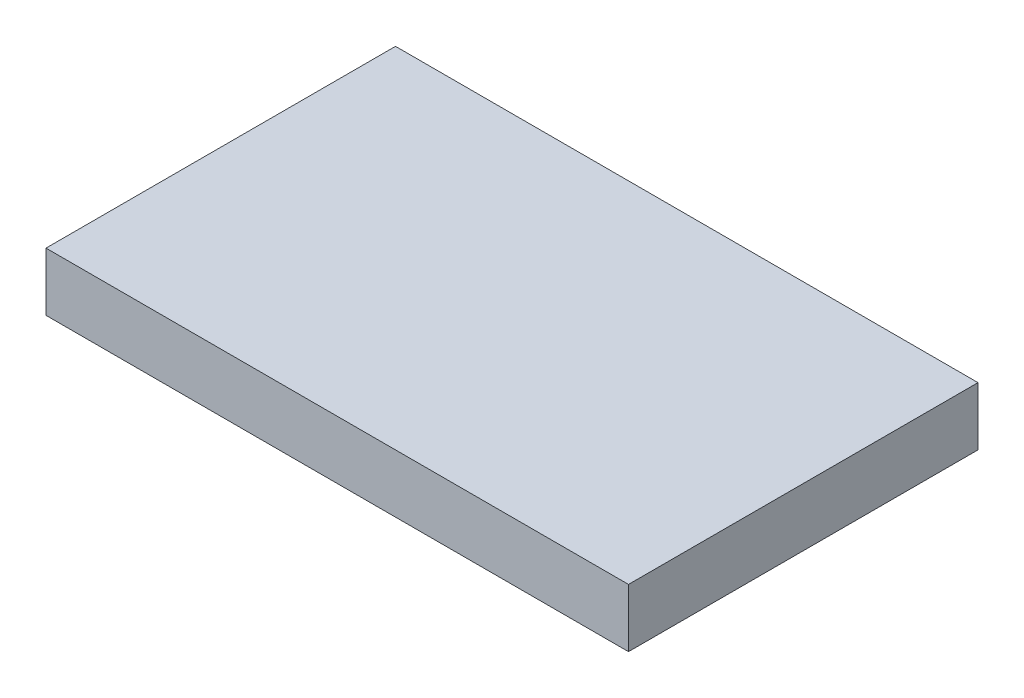
SolidWorks part; units mm, degrees
ref_plane "Front Plane" through (0, 0, 0) normal (0, 0, 1) x (1, 0, 0)
ref_plane "Top Plane" through (0, 0, 0) normal (0, 1, 0) x (1, 0, 0)
ref_plane "Right Plane" through (0, 0, 0) normal (1, 0, 0) x (0, 0, -1)
sketch "Sketch1" plane through (0, 0, 0) normal (0, 0, 1) x (1, 0, 0)
  line L1 (2.6889, 16.1056) -> (12.6889, 16.1056)
  line L2 (2.6889, 16.1056) -> (2.6889, 10.1056)
  line L3 (2.6889, 10.1056) -> (12.6889, 10.1056)
  line L4 (12.6889, 16.1056) -> (12.6889, 10.1056)
  line L5 (7.6889, 10.1056) -> (7.6889, 16.1056) construction
  line L6 (2.6889, 13.1056) -> (12.6889, 13.1056) construction
  point P104 (7.6889, 13.1056)
  dimension "D1" = 6
  dimension "D2" = 10
extrude "Boss-Extrude1" add sketch "Sketch1" along normal blind 1
move or copy body "Body-Move/Copy1" bodies to move or copy 102 copy no rotation origin (0, 13.1056, 0.25) rotation axis (1, 0, 0) rotation angle 90
